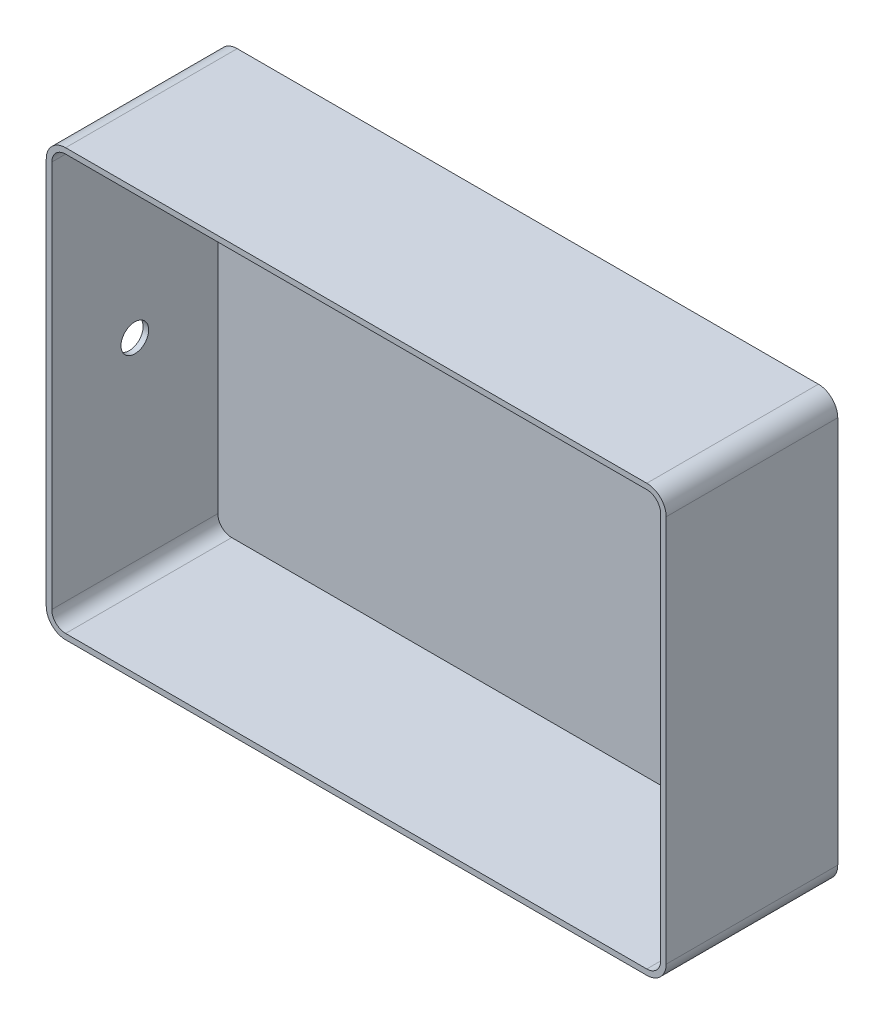
SolidWorks part; units mm, degrees
ref_plane "Front Plane" through (0, 0, 0) normal (0, 0, 1) x (1, 0, 0)
ref_plane "Top Plane" through (0, 0, 0) normal (0, 1, 0) x (1, 0, 0)
ref_plane "Right Plane" through (0, 0, 0) normal (1, 0, 0) x (0, 0, -1)
sketch "Sketch1" plane through (0, 0, 0) normal (0, 0, 1) x (1, 0, 0)
  line L1 (-105, -75) -> (105, -75)
  line L2 (-110, -70) -> (-110, 70)
  line L3 (-105, 75) -> (105, 75)
  line L4 (110, -70) -> (110, 70)
  line L5 (-110, -75) -> (110, 75) construction
  line L6 (-110, 75) -> (110, -75) construction
  arc A0 (105, -75) -> (110, -70) centre (105, -70) ccw
  arc A1 (-105, -75) -> (-110, -70) centre (-105, -70) cw
  arc A2 (105, 75) -> (110, 70) centre (105, 70) cw
  arc A3 (-110, 70) -> (-105, 75) centre (-105, 70) cw
  point P0 (0, 0)
  dimension "D3" = 5
  dimension "D1" = 150
  dimension "D2" = 220
extrude "Boss-Extrude1" add sketch "Sketch1" along normal mid plane 60
shell "Shell1" thickness 2
sketch "Sketch2" plane through (-112, 0, 0) normal (-1, 0, 0) x (0, 0, 1)
  circle A0 centre (0, 0) radius 5
  dimension "D1" = 10
extrude "Cut-Extrude1" cut sketch "Sketch2" against normal blind 50
